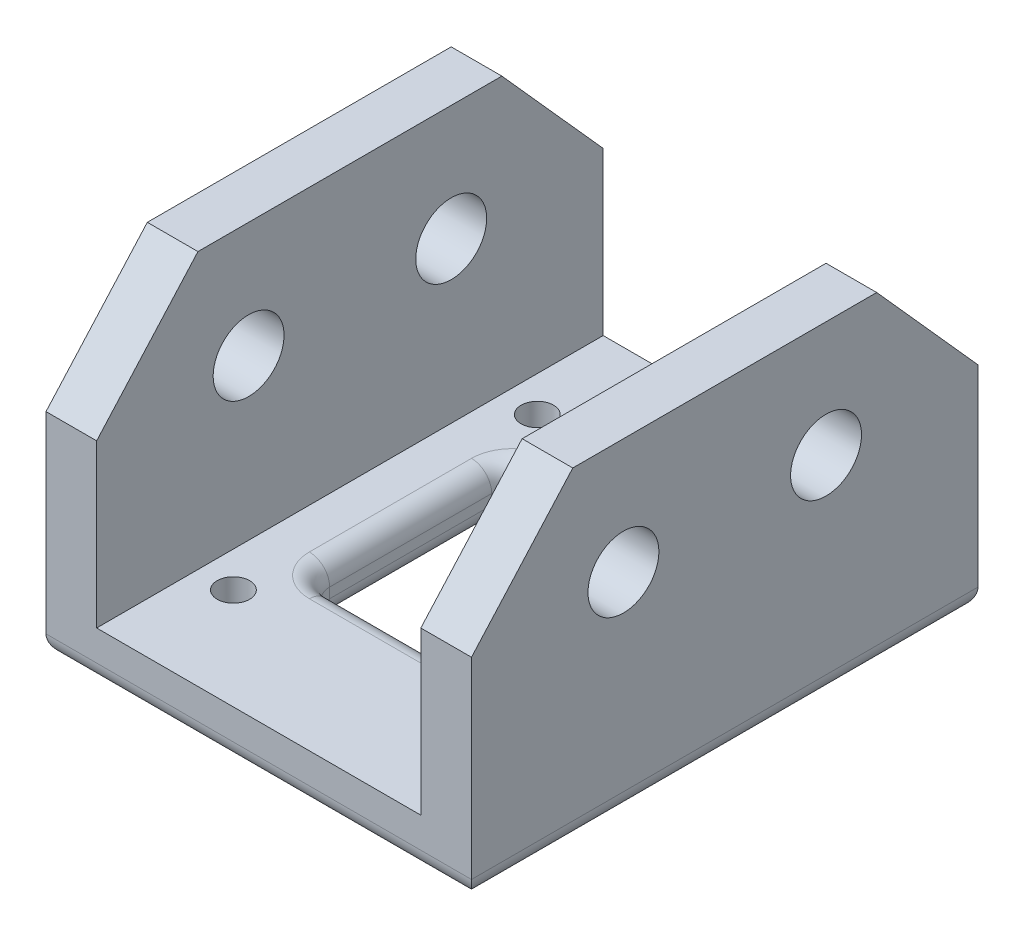
SolidWorks part; units mm, degrees
ref_plane "Front Plane" through (0, 0, 0) normal (0, 0, 1) x (1, 0, 0)
ref_plane "Top Plane" through (0, 0, 0) normal (0, 1, 0) x (1, 0, 0)
ref_plane "Right Plane" through (0, 0, 0) normal (1, 0, 0) x (0, 0, -1)
ref_plane "MiddlePlane" through (-26.67, 0, 0) normal (1, 0, 0) x (0, 0, -1)
sketch "Sketch1" plane through (0, 0, 0) normal (1, 0, 0) x (0, 0, -1)
  line L1 (0, 0) -> (63.5, 0)
  line L2 (0, 0) -> (0, 6.35)
  line L3 (0, 6.35) -> (63.5, 6.35)
  line L4 (63.5, 0) -> (63.5, 6.35)
  dimension "D1" = 6.35
  dimension "D2" = 63.5
extrude "Boss-Extrude1" add sketch "Sketch1" against normal blind 53.34
sketch "Sketch2" plane through (0, 0, 0) normal (1, 0, 0) x (0, 0, -1)
  line L0 (0, 6.35) -> (0, 26.67)
  line L1 (0, 26.67) -> (12.7, 40.869)
  line L2 (12.7, 40.869) -> (50.8, 40.869)
  line L3 (50.8, 40.869) -> (63.5, 26.67)
  line L4 (63.5, 26.67) -> (63.5, 6.35)
  line L5 (63.5, 6.35) -> (0, 6.35)
  point P7 (31.75, 40.869)
  point P10 (31.75, 6.35)
  dimension "D1" = 38.1
  dimension "D2" = 20.32
  dimension "D4" = 19.05
  dimension "D5" = 19.05
extrude "Boss-Extrude2" add sketch "Sketch2" against normal blind 6.35
sketch "Sketch11" plane through (0, 0, 0) normal (1, 0, 0) x (0, 0, -1)
  line L3 (50.8, 40.869) -> (12.7, 40.869) construction
  line L4 (0, 26.67) -> (0, 0) construction
  line L5 (63.5, 0) -> (63.5, 26.67) construction
  circle A4 centre (19.05, 26.391) radius 4.445
  circle A5 centre (44.45, 26.391) radius 4.445
  dimension "D1" = 8.89
  dimension "D3" = 19.05
  dimension "D4" = 19.05
  dimension "D2" = 14.478
extrude "Cut-Extrude1" cut sketch "Sketch11" against normal up to next
ref_plane "Plane2" through (0, 33.02, 0) normal (0, -1, 0) x (-1, 0, 0)
fillet "Fillet1" radius 2.54 4 edges at (0, 0, -31.75) (-26.67, 0, -63.5) (-53.34, 0, -31.75) (-26.67, 0, 0)
sketch "Sketch19" plane through (0, 0, 0) normal (0, -1, 0) x (1, 0, 0)
  line L0 (-26.67, -63.5) -> (-26.67, 0) construction
  line L1 (0, -63.5) -> (-53.34, -63.5) construction
  line L2 (-53.34, 0) -> (0, 0) construction
  line L3 (0, -31.75) -> (-53.34, -31.75) construction
  line L4 (0, 0) -> (0, -63.5) construction
  line L5 (-53.34, -63.5) -> (-53.34, 0) construction
  line L7 (-10.795, -50.8) -> (-42.545, -50.8) construction
  line L8 (-10.795, -50.8) -> (-10.795, -12.7) construction
  line L9 (-10.795, -12.7) -> (-42.545, -12.7) construction
  line L10 (-42.545, -50.8) -> (-42.545, -12.7) construction
  line L11 (-10.795, -50.8) -> (-42.545, -12.7) construction
  line L12 (-10.795, -12.7) -> (-42.545, -50.8) construction
  circle A0 centre (-10.795, -50.8) radius 2.032
  circle A1 centre (-42.545, -50.8) radius 2.032
  circle A2 centre (-42.545, -12.7) radius 2.032
  circle A3 centre (-10.795, -12.7) radius 2.032
  point P12 (-26.67, -31.75)
  dimension "D3" = 4.064
  dimension "D1" = 31.75
  dimension "D2" = 38.1
extrude "Cut-Extrude2" cut sketch "Sketch19" against normal up to next
mirror "Mirror1" about plane through (-26.67, 0, 0) normal (1, 0, 0) of "Cut-Extrude1", "Boss-Extrude2"
sketch "Sketch20" plane through (0, 0, 0) normal (0, -1, 0) x (1, 0, 0)
  line L0 (-2.54, -60.96) -> (-2.54, -2.54) construction
  line L1 (-16.51, -19.05) -> (-36.83, -19.05)
  line L2 (-13.97, -21.59) -> (-13.97, -41.91)
  line L3 (-16.51, -44.45) -> (-36.83, -44.45)
  line L4 (-39.37, -21.59) -> (-39.37, -41.91)
  line L5 (-50.8, -60.96) -> (-2.54, -60.96) construction
  arc A0 (-36.83, -44.45) -> (-39.37, -41.91) centre (-36.83, -41.91) cw
  arc A1 (-13.97, -41.91) -> (-16.51, -44.45) centre (-16.51, -41.91) cw
  arc A2 (-16.51, -19.05) -> (-13.97, -21.59) centre (-16.51, -21.59) cw
  arc A3 (-36.83, -19.05) -> (-39.37, -21.59) centre (-36.83, -21.59) ccw
  point P4 (-13.97, -31.75)
  point P7 (-2.54, -31.75)
  point P8 (-26.67, -44.45)
  point P11 (-26.67, -60.96)
  point P14 (-39.37, -44.45)
  point P17 (-13.97, -44.45)
  point P22 (-39.37, -19.05)
  dimension "D3" = 2.54
  dimension "D1" = 25.4
  dimension "D2" = 25.4
extrude "Cut-Extrude3" cut sketch "Sketch20" against normal up to surface (6.35 mm away) up to face at (-26.67, 6.35, -31.75)
fillet "Fillet2" radius 2.54 16 edges at (-14.7139, 6.35, -43.7061) (-26.67, 6.35, -44.45) (-38.6261, 6.35, -43.7061) (-39.37, 6.35, -31.75) (-38.6261, 6.35, -19.7939) (-26.67, 6.35, -19.05) (-14.7139, 6.35, -19.7939) (-14.7139, 0, -43.7061) (-14.7139, 0, -19.7939) (-26.67, 0, -19.05) (-38.6261, 0, -19.7939) (-39.37, 0, -31.75) (-38.6261, 0, -43.7061) (-26.67, 0, -44.45) (-13.97, 6.35, -31.75) (-13.97, 0, -31.75)
